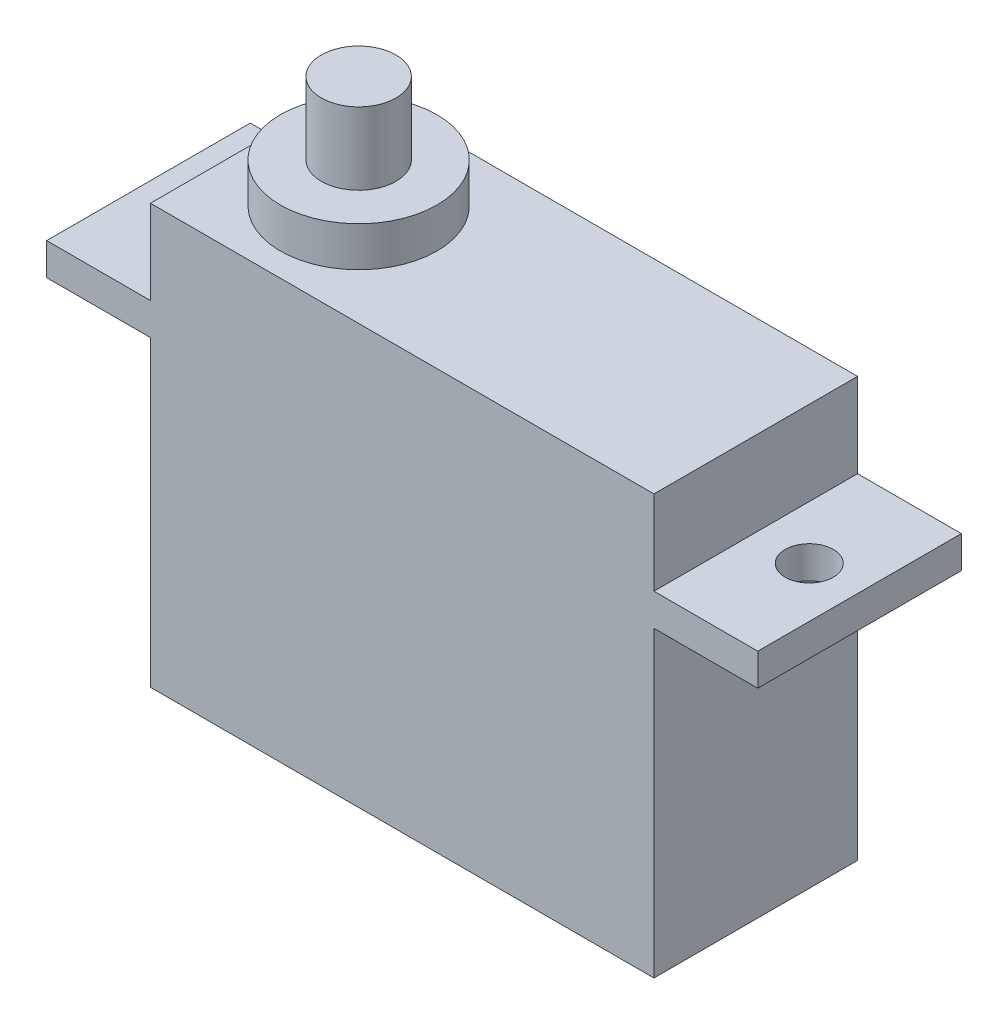
SolidWorks part; units mm, degrees
ref_plane "Front Plane" through (0, 0, 0) normal (0, 0, 1) x (1, 0, 0)
ref_plane "Top Plane" through (0, 0, 0) normal (0, 1, 0) x (1, 0, 0)
ref_plane "Right Plane" through (0, 0, 0) normal (1, 0, 0) x (0, 0, -1)
sketch "Sketch1" plane through (0, 0, 0) normal (0, 0, 1) x (1, 0, 0)
  line L0 (0, 0) -> (0, -11.32)
  line L1 (0, -11.32) -> (18.82, -11.32)
  line L2 (18.82, -11.32) -> (18.82, 0)
  line L3 (18.82, 0) -> (22.7, 0)
  line L4 (22.7, 0) -> (22.7, 1.2)
  line L5 (22.7, 1.2) -> (18.82, 1.2)
  line L6 (18.82, 1.2) -> (18.82, 4.35)
  line L7 (18.82, 4.35) -> (0, 4.35)
  line L8 (0, 4.35) -> (0, 1.2)
  line L9 (0, 1.2) -> (-3.88, 1.2)
  line L10 (-3.88, 1.2) -> (-3.88, 0)
  line L11 (-3.88, 0) -> (0, 0)
  dimension "D1" = 4.35
  dimension "D2" = 11.32
  dimension "D3" = 18.82
  dimension "D4" = 3.88
  dimension "D5" = 3.88
  dimension "D6" = 1.2
  dimension "D7" = 1.2
extrude "Boss-Extrude1" add sketch "Sketch1" along normal blind 7.61
sketch "Sketch2" plane through (0, 1.2, 0) normal (0, 1, 0) x (1, 0, 0)
  line L0 (-3.88, -3.805) -> (22.7, -3.805) construction
  line L1 (-3.88, -7.61) -> (-3.88, 0) construction
  line L2 (22.7, -7.61) -> (22.7, 0) construction
  line L6 (18.82, -7.61) -> (18.82, 0) construction
  line L7 (0, -7.61) -> (0, 0) construction
  circle A0 centre (20.82, -3.805) radius 0.9
  circle A1 centre (-2, -3.805) radius 0.9
  dimension "D1" = 1.8
  dimension "D2" = 1.8
  dimension "D4" = 2
  dimension "D3" = 2
extrude "Cut-Extrude1" cut sketch "Sketch2" against normal up to surface (1.2 mm away) up to face at (-1.94, 0, 3.805)
sketch "Sketch3" plane through (0, 4.35, 0) normal (0, 1, 0) x (1, 0, 0)
  line L0 (18.82, -3.805) -> (0, -3.805) construction
  line L1 (18.82, -7.61) -> (18.82, 0) construction
  line L2 (0, -7.61) -> (0, 0) construction
  circle A0 centre (3.9774, -3.805) radius 2.926
extrude "Boss-Extrude2" add sketch "Sketch3" along normal blind 1.49
sketch "Sketch4" plane through (0, 5.84, 0) normal (0, 1, 0) x (1, 0, 0)
  circle A0 centre (3.9774, -3.805) radius 1.3939
  circle A1 centre (3.9774, -3.805) radius 2.926 construction
extrude "Boss-Extrude3" add sketch "Sketch4" along normal blind 2.7
